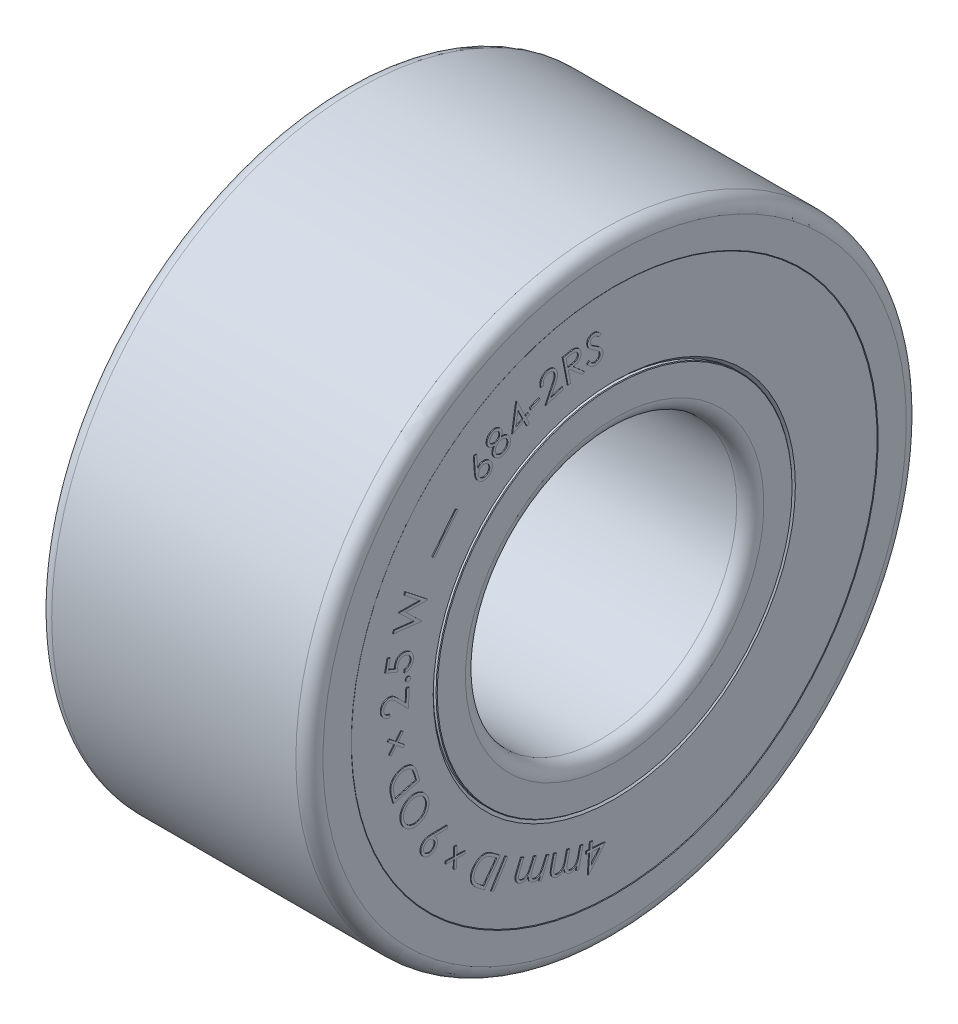
SolidWorks part; units mm, degrees
material "AISI 316 Annealed Stainless Steel Bar (SS)"
ref_plane "Front" through (0, 0, 0) normal (0, 0, 1) x (1, 0, 0)
ref_plane "Top" through (0, 0, 0) normal (0, 1, 0) x (1, 0, 0)
ref_plane "Right" through (0, 0, 0) normal (1, 0, 0) x (0, 0, -1)
sketch "LAYOUT R" plane through (0, 0, 0) normal (1, 0, 0) x (0, 0, -1)
  line L0 (-2, 2) -> (2, 2)
  line L1 (2, -4.5) -> (-2, -4.5) construction
  line L2 (2, -4.5) -> (2, 4.5) construction
  line L3 (2, 4.5) -> (-2, 4.5)
  line L4 (-2, -4.5) -> (-2, 4.5) construction
  line L5 (2, -4.5) -> (-2, 4.5) construction
  line L6 (2, 4.5) -> (-2, -4.5) construction
  line L7 (-2, 2.625) -> (2, 2.625)
  line L8 (-2, 3.875) -> (2, 3.875)
  line L11 (-3.81, 0) -> (3.81, 0) construction
  line L12 (-2, 4.5) -> (-2, 3.875)
  line L13 (2, 4.5) -> (2, 3.875)
  line L14 (-2, 3.875) -> (-2, 2.625)
  line L15 (2, 3.875) -> (2, 2.625)
  line L16 (-2, 2.625) -> (-2, 2)
  line L17 (2, 2.625) -> (2, 2)
  line L18 (-1.9945, 3.875) -> (-1.9945, 2.625)
  line L19 (1.9945, 3.875) -> (1.9945, 2.625)
  point P0 (0, 0)
  point P15 (0, 0)
  dimension "D1" = 4
  dimension "D2" = 9
  dimension "D3" = 2
  dimension "D6" = 0.0055
  dimension "D7" = 0.0055
  dimension "D4" = 2.625
  dimension "D5" = 3.875
sketch "Sketch R, INNER BODY" plane through (0, 0, 0) normal (1, 0, 0) x (0, 0, -1)
  line L0 (-2, 2) -> (2, 2) construction
  line L2 (-2, 2.625) -> (2, 2.625) construction
  line L4 (-2, 2) -> (2, 2)
  line L6 (-2, 2.625) -> (2, 2.625)
  line L8 (2, 2.625) -> (2, 2) construction
  line L9 (-2, 2.625) -> (-2, 2) construction
  line L10 (2, 2.625) -> (2, 2)
  line L11 (-2, 2.625) -> (-2, 2)
  line L12 (-3.81, 0) -> (3.81, 0) construction
  line L13 (-3.81, 0) -> (3.81, 0) construction
sketch "Sketch R, OUTER BODY" plane through (0, 0, 0) normal (1, 0, 0) x (0, 0, -1)
  line L0 (-2, 3.875) -> (2, 3.875) construction
  line L1 (2, 4.5) -> (2, 3.875) construction
  line L8 (-3.81, 0) -> (3.81, 0) construction
  line L9 (-3.81, 0) -> (3.81, 0) construction
  line L16 (2, 4.5) -> (-2, 4.5) construction
  line L17 (-2, 4.5) -> (-2, 3.875) construction
  line L18 (-2, 3.875) -> (2, 3.875)
  line L19 (2, 4.5) -> (2, 3.875)
  line L22 (2, 4.5) -> (-2, 4.5)
  line L23 (-2, 4.5) -> (-2, 3.875)
sketch "Sketch R, SEAL FACES" plane through (0, 0, 0) normal (1, 0, 0) x (0, 0, -1)
  line L0 (-3.81, 0) -> (3.81, 0) construction
  line L1 (-3.81, 0) -> (3.81, 0) construction
  line L3 (-2, 2.625) -> (2, 2.625) construction
  line L5 (-2, 3.875) -> (2, 3.875) construction
  line L7 (-1.9945, 2.625) -> (1.9945, 2.625)
  line L9 (-1.9945, 3.875) -> (1.9945, 3.875)
  line L10 (1.9945, 3.875) -> (1.9945, 2.625) construction
  line L11 (-1.9945, 3.875) -> (-1.9945, 2.625) construction
  line L12 (1.9945, 3.875) -> (1.9945, 2.625)
  line L13 (-1.9945, 3.875) -> (-1.9945, 2.625)
revolve "Revolve INNER BODY" add sketch "Sketch R, INNER BODY" angle 360 about L13
fillet "Fillet INNER BODY" radius 0.2 2 edges at (0, -2, 2) (0, -2, -2)
chamfer "Chamfer INNER BODY" distance 0.009 angle 45 2 edges at (0, -2.625, -2) (0, -2.625, 2)
revolve "Revolve OUTER BODY" add sketch "Sketch R, OUTER BODY" angle 360 about L9
fillet "Fillet OUTER BODY" radius 0.2 2 edges at (0, -4.5, 2) (0, -4.5, -2)
chamfer "Chamfer OUTER BODY" distance 0.009 angle 45 2 edges at (0, -3.875, 2) (0, -3.875, -2)
revolve "Revolve SEALS" add sketch "Sketch R, SEAL FACES" angle 360 about L1
chamfer "Chamfer SEALS" distance 0.045 angle 45 2 edges at (0, -2.625, -1.9945) (0, -2.625, 1.9945)
sketch "Sketch TEXT RADIUS 1 — MANUALLY ASSIGN TEXT AND FONT SIZE (FROM EQUATIONS)" plane through (0, 0, 1.9945) normal (0, 0, 1) x (1, 0, 0)
  circle A0 centre (0, 0) radius 3.05 construction
  text T0 "4mm ID × 9 OD × 2.5 W  —  684-2RS" font "Century Gothic" height 0.4
  dimension "D1" = 6.1
extrude "Boss-Extrude SEAL LABEL 1" add sketch "Sketch TEXT RADIUS 1 — MANUALLY ASSIGN TEXT AND FONT SIZE (FROM EQUATIONS)" along normal blind 0.013
sketch "Sketch TEXT RADIUS 2 — MANUALLY ASSIGN TEXT AND FONT SIZE (FROM EQUATIONS)" plane through (0, 0, -1.9945) normal (0, 0, -1) x (-1, 0, 0)
  circle A0 centre (0, 0) radius 3.05 construction
  text T0 "4mm ID × 9 OD × 2.5 W  —  684-2RS" font "Century Gothic" height 0.4
  dimension "D1" = 6.1
extrude "Boss-Extrude SEAL LABEL 2" add sketch "Sketch TEXT RADIUS 2 — MANUALLY ASSIGN TEXT AND FONT SIZE (FROM EQUATIONS)" along normal blind 0.013
move or copy body "Body-Move/Copy1" bodies to move or copy 147 copy no rotation origin (0, 0, 0) rotation axis (0, 1, 0) rotation angle 90
equation "\"_i__BORE\"= 4"
equation "\"_i__OUTSIDE_DIAMETER\"= 9"
equation "\"_i__WIDTH\"= 4"
equation "\"_user_applied_FONT_SIZE\"= int ( \"BODY_SPAN__SEAL__OF_RADIUS\" * \"g_param__FONT_SIZE_RATIO\" * 100 ) / 100'MANUALLY ASSIGN TO FONT"
equation "\"BODY__HALF_WIDTH\"= \"_i__WIDTH\" / 2"
equation "\"BODY_SPAN___OF_DIAMETER\"= \"_i__OUTSIDE_DIAMETER\" - \"_i__BORE\""
equation "\"BODY_SPAN___OF_RADIUS\"= \"BODY_SPAN___OF_DIAMETER\" / 2"
equation "\"BODY_SPAN__BORE_AND_OD__OF RADIUS\"= ( \"BODY_SPAN___OF_RADIUS\" - \"BODY_SPAN__SEAL__OF_RADIUS\" ) / 2"
equation "\"BODY_SPAN__SEAL__OF_RADIUS\"= \"BODY_SPAN___OF_RADIUS\" * \"g_param__SEAL_PANEL_SPAN__RATIO_OF_BODY_RADIAN\""
equation "\"BORE__RADIUS\"= \"_i__BORE\" / 2"
equation "\"CORNER_RADII\"= \"_i__WIDTH\" * \"g_param__CORNER_RADII__RATIO_TO_WIDTH\""
equation "\"RING_INNER__OUTSIDE_RADIUS\"= \"BORE__RADIUS\" + \"BODY_SPAN__BORE_AND_OD__OF RADIUS\""
equation "\"RING_OUTER__OUTSIDE_RADIUS\"= ( \"_i__OUTSIDE_DIAMETER\" / 2 ) - \"BODY_SPAN__BORE_AND_OD__OF RADIUS\""
equation "\"SEAL_CHAMFERS\"= \"_i__OUTSIDE_DIAMETER\" * \"g_param__SEAL_CHAMFERS__RATIO_TO_OD\""
equation "\"SEAL_FACE_INSET\"= \"SIDE_FACE_CHAMFERS\""
equation "\"SIDE_FACE_CHAMFERS\"= \"_i__OUTSIDE_DIAMETER\" * \"g_param__SIDE_CHAMFERS__RATIO_TO_OD\""
equation "\"TEXT_RADIUS\"= \"_i__BORE\" + ( \"BODY_SPAN___OF_DIAMETER\" / 2 ) - \"_user_applied_FONT_SIZE\""
equation "\"D1@Boss-Extrude SEAL LABEL 1\" = \"g_param__INDICIA__EXTRUSION_HEIGHT\""
equation "\"D1@Boss-Extrude SEAL LABEL 2\" = \"g_param__INDICIA__EXTRUSION_HEIGHT\""
equation "\"D1@Chamfer INNER BODY\"=\"SIDE_FACE_CHAMFERS\""
equation "\"D1@Chamfer OUTER BODY\"=\"SIDE_FACE_CHAMFERS\""
equation "\"D1@Chamfer SEALS\"=\"SEAL_CHAMFERS\""
equation "\"D1@Fillet INNER BODY\"=\"CORNER_RADII\""
equation "\"D1@Fillet OUTER BODY\"=\"CORNER_RADII\""
equation "\"D1@LAYOUT R\"=\"_i__WIDTH\""
equation "\"D1@Sketch TEXT RADIUS 1 — MANUALLY ASSIGN TEXT AND FONT SIZE (FROM EQUATIONS)\" = \"TEXT_RADIUS\""
equation "\"D1@Sketch TEXT RADIUS 2 — MANUALLY ASSIGN TEXT AND FONT SIZE (FROM EQUATIONS)\" = \"TEXT_RADIUS\""
equation "\"D2@LAYOUT R\"=\"_i__OUTSIDE_DIAMETER\""
equation "\"D3@LAYOUT R\"=\"BORE__RADIUS\""
equation "\"D4@LAYOUT R\"=\"RING_INNER__OUTSIDE_RADIUS\""
equation "\"D5@LAYOUT R\"=\"RING_OUTER__OUTSIDE_RADIUS\""
equation "\"g_param__CORNER_RADII__RATIO_TO_WIDTH\"= 0.05'ISO MAX IS 0.07 WHERE WIDTH IS LESS THAN DIAMETER"
equation "\"g_param__FONT_SIZE_RATIO\"= 0.32'EXPRESSES RADIAL PROPORTION OF SEAL FACE"
equation "\"g_param__INDICIA__EXTRUSION_HEIGHT\"=0.013'RAISED INDICIA ON SEAL FACES"
equation "\"g_param__SEAL_CHAMFERS__RATIO_TO_OD\"= 0.005"
equation "\"g_param__SEAL_PANEL_SPAN__RATIO_OF_BODY_RADIAN\"= 0.5'ISO-UNSPECIFIED"
equation "\"g_param__SIDE_CHAMFERS__RATIO_TO_OD\"= 0.001'NOT ISO-SPECIFIED"
